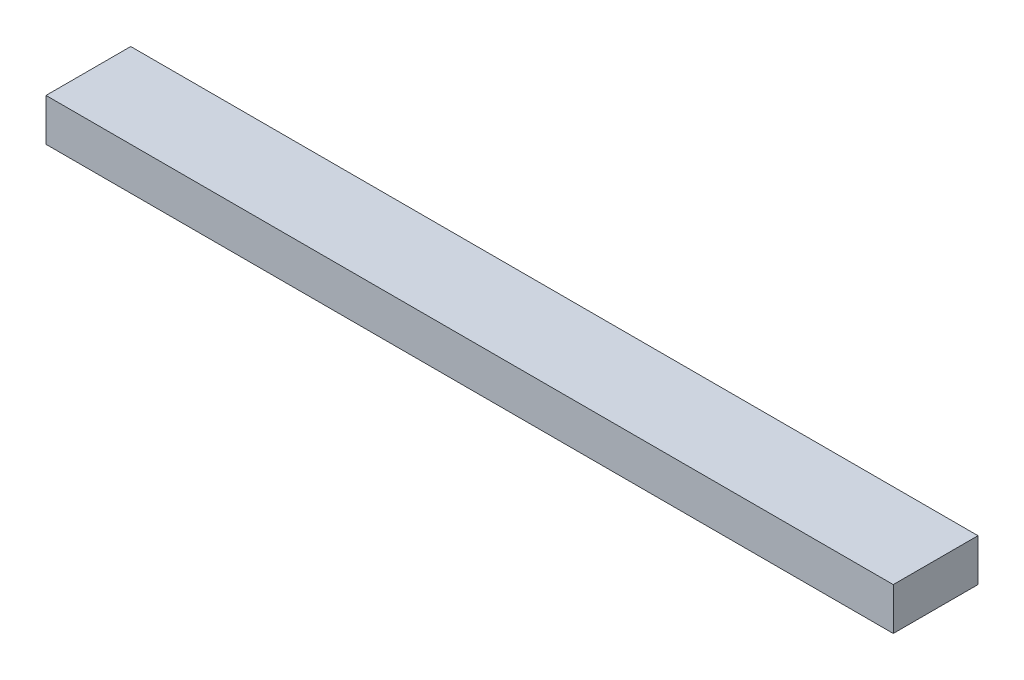
SolidWorks part; units mm, degrees
ref_plane "Front Plane" through (0, 0, 0) normal (0, 0, 1) x (1, 0, 0)
ref_plane "Top Plane" through (0, 0, 0) normal (0, 1, 0) x (1, 0, 0)
ref_plane "Right Plane" through (0, 0, 0) normal (1, 0, 0) x (0, 0, -1)
sketch "Sketch1" plane through (0, 0, 0) normal (0, 1, 0) x (1, 0, 0)
  line L1 (0, 0) -> (254, 0)
  line L2 (0, 0) -> (0, 25.4)
  line L3 (0, 25.4) -> (254, 25.4)
  line L4 (254, 0) -> (254, 25.4)
  dimension "D1" = 254
  dimension "D2" = 25.4
extrude "Boss-Extrude1" add sketch "Sketch1" along normal blind 12.7
